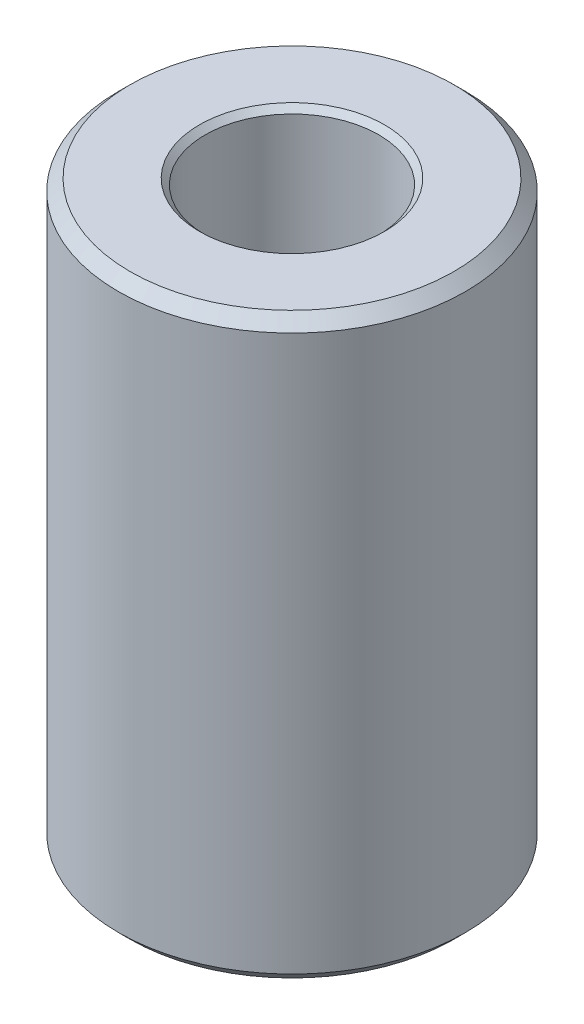
SolidWorks part; units mm, degrees
ref_plane "前视基准面" through (0, 0, 0) normal (0, 0, 1) x (1, 0, 0)
ref_plane "上视基准面" through (0, 0, 0) normal (0, 1, 0) x (1, 0, 0)
ref_plane "右视基准面" through (0, 0, 0) normal (1, 0, 0) x (0, 0, -1)
other "Configuration Table"
sketch "草图1" plane through (0, 0, 0) normal (0, 1, 0) x (1, 0, 0)
  circle A0 centre (0, 0) radius 3
  dimension "D1" = 6
extrude "凸台-拉伸1" add sketch "草图1" along normal blind 10
sketch "草图2" plane through (0, 0, 0) normal (0, 1, 0) x (1, 0, 0)
  circle A0 centre (0, 0) radius 1
  dimension "D1" = 2
extrude "切除-拉伸1" cut sketch "草图2" along normal blind 5
sketch "草图3" plane through (0, 0, 0) normal (0, 1, 0) x (1, 0, 0)
  circle A0 centre (0, 0) radius 1.5
  dimension "D1" = 3
extrude "切除-拉伸2" cut sketch "草图3" against normal blind 5 from surface at 10 starting at face at (0, 10, 3)
chamfer "倒角1" distance 0.2 angle 45 2 edges at (0, 10, 3) (0, 0, 3)
chamfer "倒角2" distance 0.1 angle 45 2 edges at (0, 0, 1) (0, 10, 1.5)
